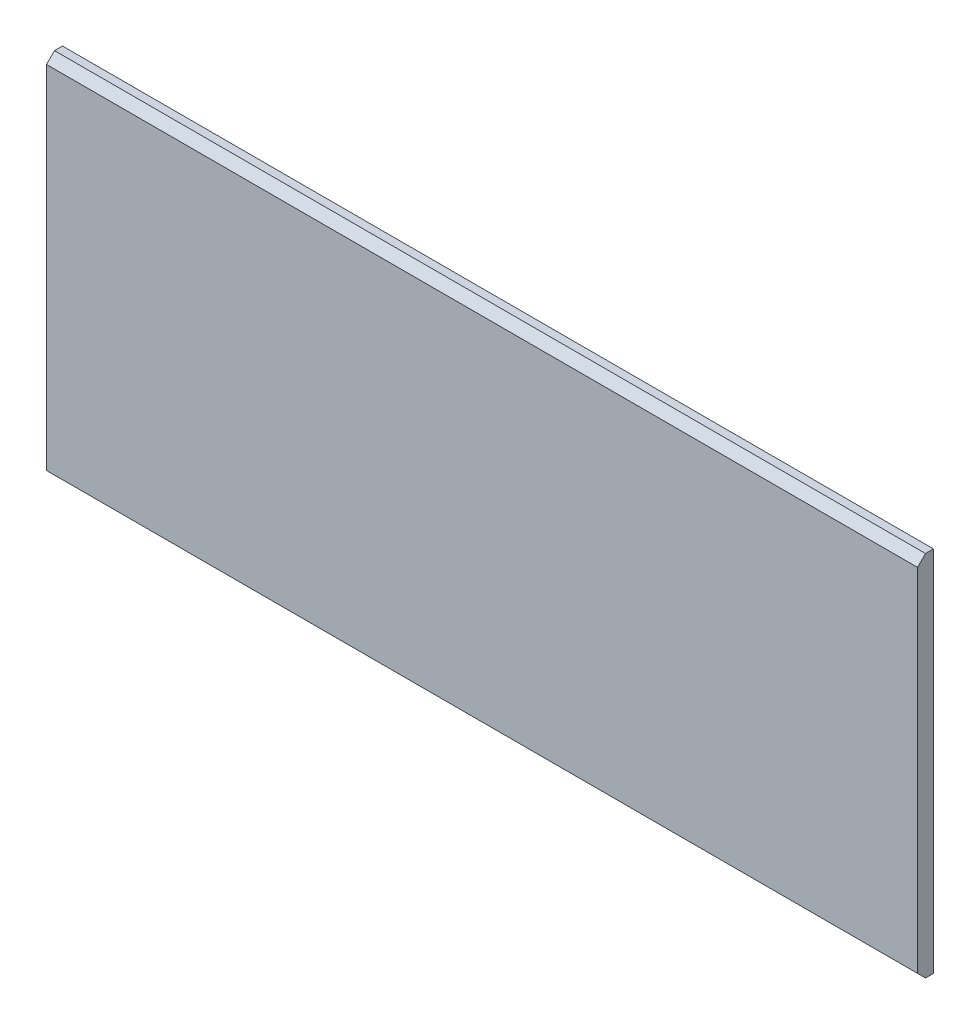
SolidWorks part; units mm, degrees
ref_plane "前视基准面" through (0, 0, 0) normal (0, 0, 1) x (1, 0, 0)
ref_plane "上视基准面" through (0, 0, 0) normal (0, 1, 0) x (1, 0, 0)
ref_plane "右视基准面" through (0, 0, 0) normal (1, 0, 0) x (0, 0, -1)
sketch "草图1" plane through (0, 0, 0) normal (0, 0, 1) x (1, 0, 0)
  line L1 (-272.5, 115) -> (272.5, 115)
  line L2 (-272.5, 115) -> (-272.5, -115)
  line L3 (-272.5, -115) -> (272.5, -115)
  line L4 (272.5, 115) -> (272.5, -115)
  line L5 (-272.5, 115) -> (272.5, -115) construction
  line L6 (-272.5, -115) -> (272.5, 115) construction
  point P0 (0, 0)
  dimension "D1" = 545
  dimension "D2" = 230
extrude "凸台-拉伸1" add sketch "草图1" along normal blind 10
chamfer "倒角1" distance 5 angle 45 2 edges at (0, 115, 10) (0, -115, 10)
